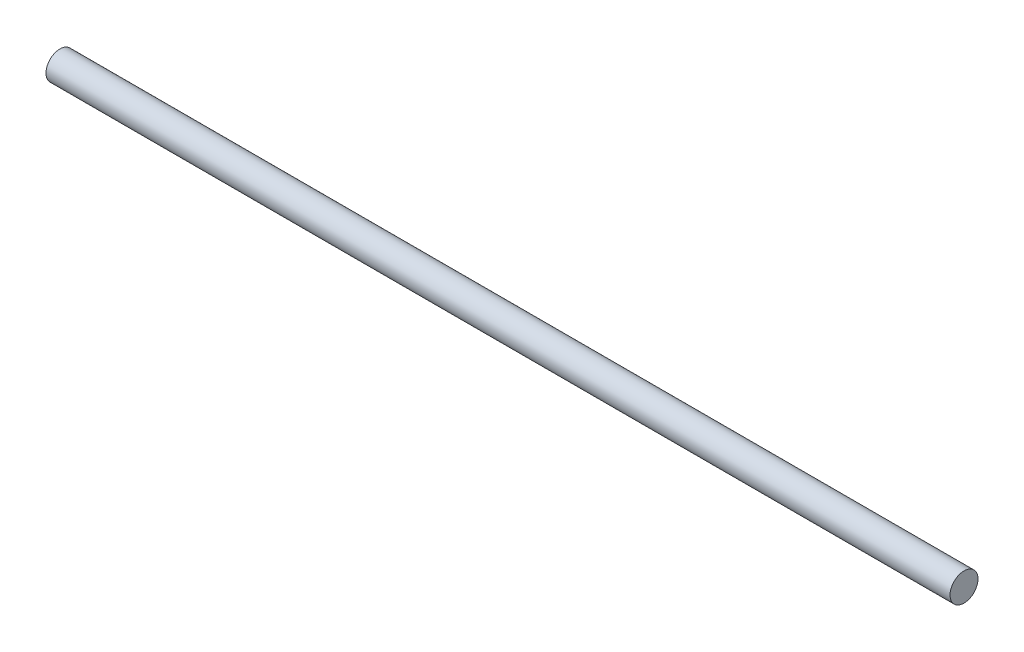
SolidWorks part; units mm, degrees
ref_plane "Front Plane" through (0, 0, 0) normal (0, 0, 1) x (1, 0, 0)
ref_plane "Top Plane" through (0, 0, 0) normal (0, 1, 0) x (1, 0, 0)
ref_plane "Right Plane" through (0, 0, 0) normal (1, 0, 0) x (0, 0, -1)
sketch "Sketch1" plane through (0, 0, 0) normal (1, 0, 0) x (0, 0, -1)
  circle A0 centre (0, 0) radius 1.5
  dimension "D1" = 3
extrude "Boss-Extrude1" add sketch "Sketch1" along normal blind 97
